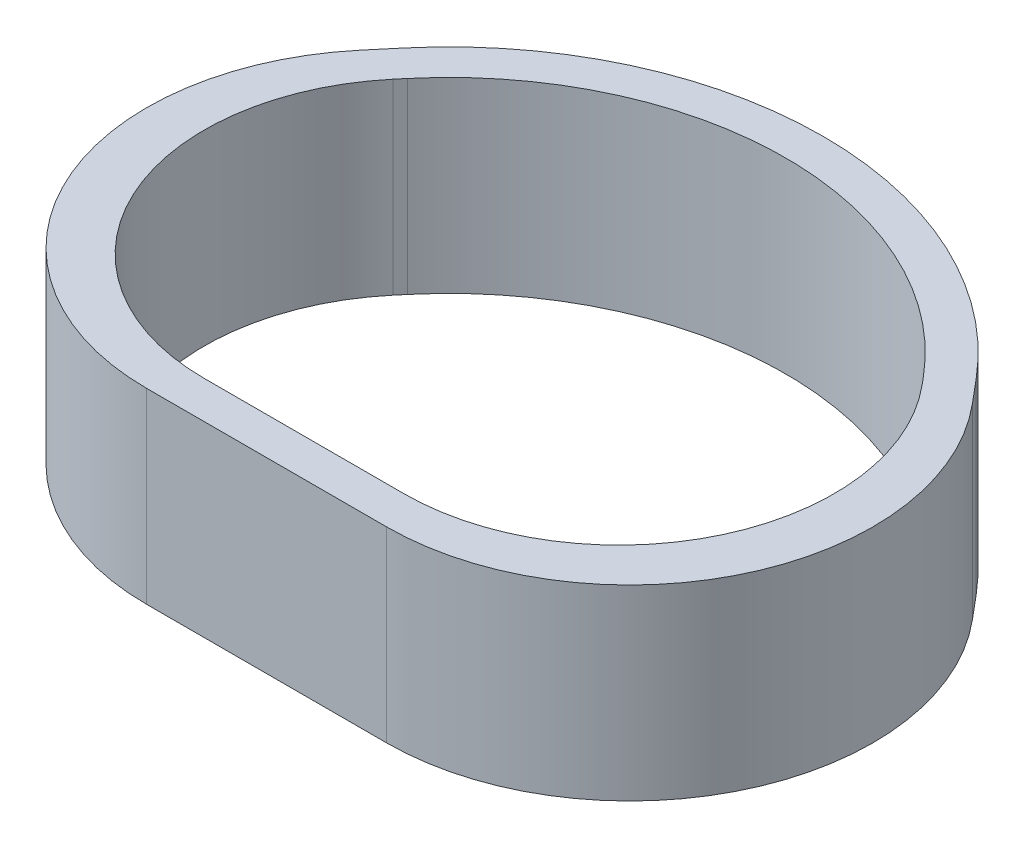
SolidWorks part; units mm, degrees
ref_plane "前视基准面" through (0, 0, 0) normal (0, 0, 1) x (1, 0, 0)
ref_plane "上视基准面" through (0, 0, 0) normal (0, 1, 0) x (1, 0, 0)
ref_plane "右视基准面" through (0, 0, 0) normal (1, 0, 0) x (0, 0, -1)
other "Configuration Table"
sketch "草图1" plane through (0, 0, 0) normal (0, 1, 0) x (1, 0, 0)
  line L0 (-53.3817, 0) -> (53.3817, 0)
  line L1 (0, -1000) -> (0, 49000) construction
  line L2 (-141.4768, 188.9206) -> (-137.888, 193.1976)
  line L3 (137.888, 193.1976) -> (141.4768, 188.9206)
  arc A0 (53.3817, 0) -> (141.4768, 188.9206) centre (53.3817, 115) ccw
  arc A1 (-53.3817, 0) -> (-141.4768, 188.9206) centre (-53.3817, 115) cw
  arc A2 (-137.888, 193.1976) -> (137.888, 193.1976) centre (0, 77.4958) cw
  point P6 (0, 0)
  point P7 (-59.2804, 0)
  point P10 (300, 0)
  point P13 (-300, 0)
  point P16 (0, 357.5261)
  dimension "D3" = 115
  dimension "D4" = 180
  dimension "D1" = 50
  dimension "D2" = 600
sketch "草图2" plane through (0, 0, 0) normal (0, 1, 0) x (1, 0, 0)
  line L0 (141.4768, 188.9206) -> (137.888, 193.1976)
  line L1 (-137.888, 193.1976) -> (-141.4768, 188.9206)
  line L2 (-53.3817, 0) -> (53.3817, 0)
  line L3 (153.2089, 206.0533) -> (163.69, 193.5624)
  line L4 (0, -201000) -> (0, 249000) construction
  line L5 (64.1042, -20) -> (-64.1042, -20)
  line L6 (-163.69, 193.5624) -> (-153.2089, 206.0533)
  arc A0 (137.888, 193.1976) -> (-137.888, 193.1976) centre (0, 77.4958) ccw
  arc A1 (-141.4768, 188.9206) -> (-53.3817, 0) centre (-53.3817, 115) ccw
  arc A2 (141.4768, 188.9206) -> (53.3817, 0) centre (53.3817, 115) cw
  arc A3 (-64.1042, -20) -> (-163.69, 193.5624) centre (-64.1042, 110) cw
  arc A4 (163.69, 193.5624) -> (64.1042, -20) centre (64.1042, 110) cw
  arc A5 (153.2089, 206.0533) -> (-153.2089, 206.0533) centre (0, 77.4958) ccw
  point P9 (0, 357.5261)
  point P12 (-300, 0)
  point P15 (300, 0)
  point P26 (0, 388.6406)
  dimension "D1" = 180
  dimension "D2" = 115
  dimension "D5" = 130
  dimension "D6" = 200
  dimension "D3" = 20
  dimension "D4" = 20
extrude "凸台-拉伸1" add sketch "草图2" along normal blind 100
